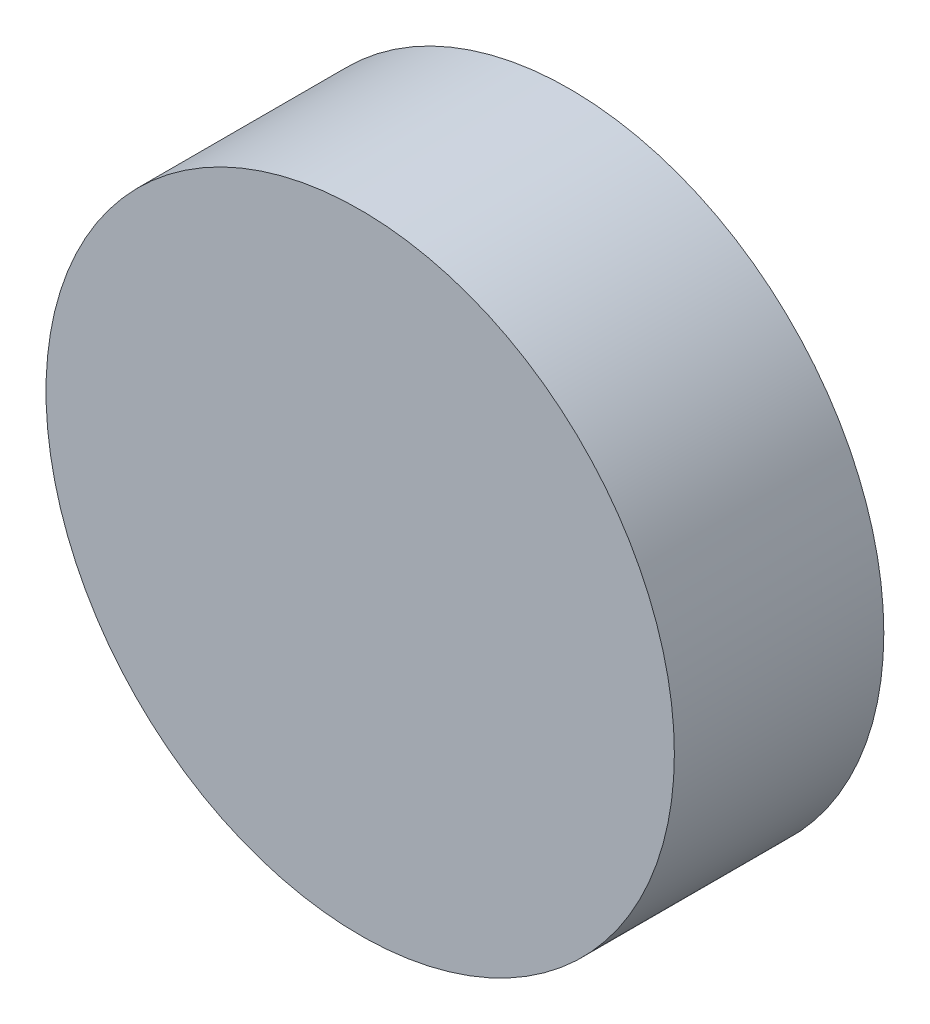
SolidWorks part; units mm, degrees
ref_plane "前视基准面" through (0, 0, 0) normal (0, 0, 1) x (1, 0, 0)
ref_plane "上视基准面" through (0, 0, 0) normal (0, 1, 0) x (1, 0, 0)
ref_plane "右视基准面" through (0, 0, 0) normal (1, 0, 0) x (0, 0, -1)
other "Configuration Table"
sketch "草图1" plane through (0, 0, 0) normal (0, 0, 1) x (1, 0, 0)
  circle A0 centre (0, 0) radius 7.5
  dimension "diameter" = 15
extrude "Lens" add sketch "草图1" along normal blind 5
